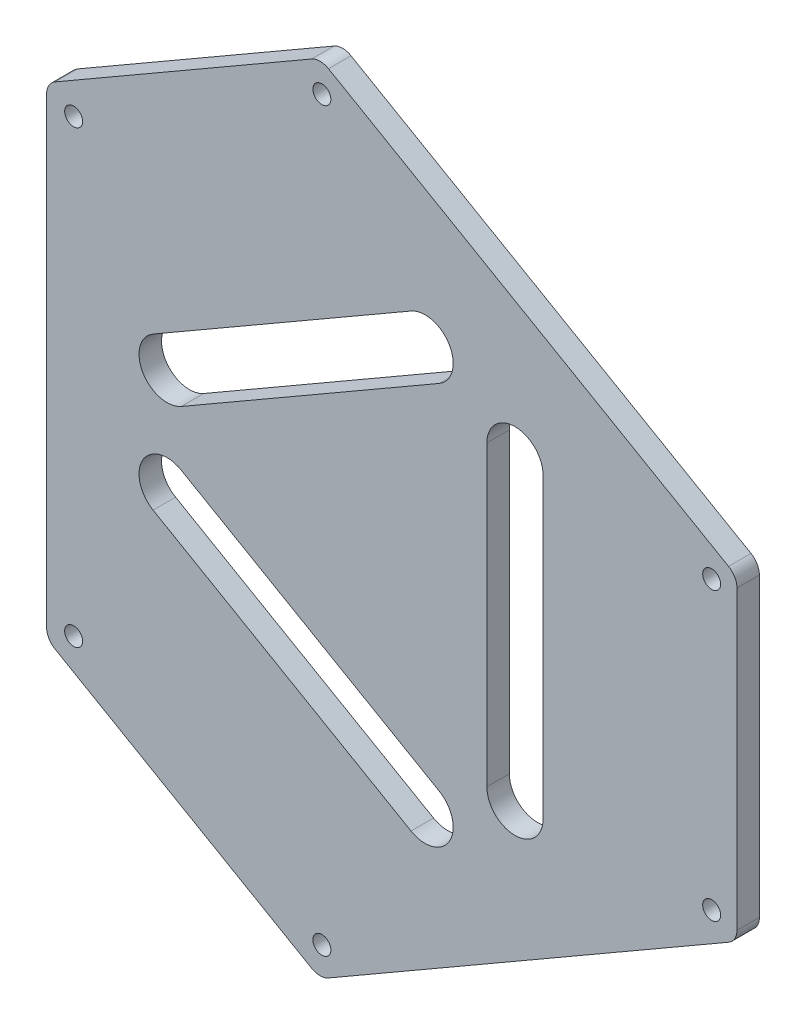
SolidWorks part; units mm, degrees
material "有机玻璃 (TM) GS 丙烯酸铸钣"
ref_plane "前视基准面" through (0, 0, 0) normal (0, 0, 1) x (1, 0, 0)
ref_plane "上视基准面" through (0, 0, 0) normal (0, 1, 0) x (1, 0, 0)
ref_plane "右视基准面" through (0, 0, 0) normal (1, 0, 0) x (0, 0, -1)
sketch "草图1" plane through (0, 0, 0) normal (0, 0, 1) x (1, 0, 0)
  line L0 (0, 0) -> (-67.3124, 0) construction
  line L1 (134.6248, 0) -> (-67.3124, 116.5885)
  line L2 (-67.3124, 116.5885) -> (-67.3124, -116.5885)
  line L3 (-67.3124, -116.5885) -> (134.6248, 0)
  line L4 (-67.3124, 116.5885) -> (-67.3124, 85.5885) construction
  line L5 (-67.3124, 85.5885) -> (-67.3124, 45.5885) construction
  line L6 (0, 0) -> (117.3042, 0) construction
  line L7 (117.3042, 10) -> (117.3042, -10)
  line L8 (-49.9919, -106.5885) -> (-67.3124, -96.5885)
  line L9 (-58.6521, -101.5885) -> (-67.3124, -116.5885) construction
  line L10 (0, 0) -> (-58.6521, -101.5885) construction
  line L11 (-67.3124, 96.5885) -> (-49.9919, 106.5885)
  line L12 (85.9645, 5) -> (-38.6521, 76.9474)
  line L13 (-47.3124, 71.9474) -> (-47.3124, -71.9474)
  line L14 (-38.6521, -76.9474) -> (85.9645, -5)
  line L15 (85.9645, 5) -> (85.9645, -5)
  line L16 (-38.6521, -76.9474) -> (-47.3124, -71.9474)
  line L17 (-47.3124, 71.9474) -> (-38.6521, 76.9474)
  line L18 (94.6248, 0) -> (-47.3124, 81.9474) construction
  line L19 (-47.3124, 81.9474) -> (-47.3124, -81.9474) construction
  line L20 (-47.3124, -81.9474) -> (94.6248, 0) construction
  line L24 (117.3042, 0) -> (134.6248, 0) construction
  line L25 (-58.6521, 101.5885) -> (-67.3124, 116.5885) construction
  line L26 (0, 0) -> (-58.6521, 101.5885) construction
  line L27 (60.9645, -25.5) -> (60.9645, 25.5) construction
  line L28 (60.9645, 0) -> (40.4645, 0) construction
  line L29 (81.4645, 4.5) -> (81.4645, 7.5981)
  line L30 (81.4645, -4.5) -> (81.4645, -7.5981)
  line L31 (35.9645, 33.8675) -> (35.9645, -33.8675)
  line L32 (44.9645, 28.6714) -> (44.9645, -28.6714)
  line L33 (11.3479, -48.0799) -> (-47.3124, -14.2124)
  line L34 (2.3479, -53.2761) -> (-47.3124, -24.6047)
  line L35 (-52.5659, -40.0468) -> (-8.3986, -65.5468) construction
  line L36 (-44.6294, -68.3003) -> (-47.3124, -66.7513)
  line L37 (-36.8351, -72.8003) -> (-34.1521, -74.3494)
  line L38 (-47.3124, 14.2124) -> (11.3479, 48.0799)
  line L39 (-47.3124, 24.6047) -> (2.3479, 53.2761)
  line L40 (-8.3986, 65.5468) -> (-52.5659, 40.0468) construction
  line L41 (-36.8351, 72.8003) -> (-34.1521, 74.3494)
  line L42 (-44.6294, 68.3003) -> (-47.3124, 66.7513)
  line L43 (40.4645, 22) -> (40.4645, -22) construction
  line L44 (60.9645, 25.5) -> (41.9119, 36.5) construction
  line L45 (-8.3986, -65.5468) -> (10.654, -54.5468) construction
  line L46 (-1.1797, -46.0433) -> (-39.2848, -24.0433) construction
  line L47 (-52.5659, 40.0468) -> (-52.5659, 18.0468) construction
  line L48 (-39.2848, 24.0433) -> (-1.1797, 46.0433) construction
  line L49 (65.4645, 28.0981) -> (65.4645, -28.0981)
  line L50 (-8.7186, -70.9277) -> (-57.3859, -42.8296)
  line L51 (-57.3859, 42.8296) -> (-8.7186, 70.9277)
  line L52 (65.4645, 28.0981) -> (-8.7186, 70.9277)
  line L53 (-57.3859, 42.8296) -> (-57.3859, -42.8296)
  line L54 (65.4645, -28.0981) -> (-8.7186, -70.9277)
  line L55 (25.9645, 26.5) -> (25.9645, -26.5) construction
  line L56 (30.9645, 26.5) -> (30.9645, -26.5)
  line L57 (20.9645, 26.5) -> (20.9645, -26.5)
  line L58 (9.9674, -35.7359) -> (-35.9319, -9.2359) construction
  line L59 (7.4674, -40.066) -> (-38.4319, -13.566)
  line L60 (12.4674, -31.4058) -> (-33.4319, -4.9058)
  line L61 (-35.9319, 9.2359) -> (9.9674, 35.7359) construction
  line L62 (-38.4319, 13.566) -> (7.4674, 40.066)
  line L63 (-33.4319, 4.9058) -> (12.4674, 31.4058)
  circle A0 centre (0, 0) radius 67.3124 construction
  circle A1 centre (-59.9021, 103.7535) radius 2.5
  circle A2 centre (-59.9021, 103.7535) radius 10.3078
  circle A3 centre (119.8042, 0) radius 10.3078
  circle A4 centre (119.8042, 0) radius 2.5
  circle A5 centre (-59.9021, -103.7535) radius 10.3078
  circle A6 centre (-59.9021, -103.7535) radius 2.5
  circle A7 centre (40.4645, 0) radius 1.6
  circle A8 centre (60.9645, 25.5) radius 1.6
  circle A9 centre (81.4645, 0) radius 1.6
  circle A10 centre (81.4645, 0) radius 4.5
  circle A11 centre (60.9645, -25.5) radius 1.6
  circle A12 centre (-20.2323, -35.0433) radius 1.6
  circle A13 centre (-8.3986, -65.5468) radius 1.6
  circle A14 centre (-52.5659, -40.0468) radius 1.6
  circle A15 centre (-40.7323, -70.5503) radius 4.5
  circle A16 centre (-40.7323, -70.5503) radius 1.6
  circle A17 centre (-20.2323, 35.0433) radius 1.6
  circle A18 centre (-52.5659, 40.0468) radius 1.6
  circle A19 centre (-8.3986, 65.5468) radius 1.6
  circle A20 centre (-40.7323, 70.5503) radius 4.5
  circle A21 centre (-40.7323, 70.5503) radius 1.6
  circle A22 centre (40.4645, -22) radius 1.6
  circle A23 centre (40.4645, 22) radius 1.6
  circle A24 centre (41.9119, 36.5) radius 1.6
  circle A25 centre (41.9119, -36.5) radius 1.6
  circle A26 centre (-52.5659, -18.0468) radius 1.6
  circle A27 centre (10.654, -54.5468) radius 1.6
  circle A28 centre (-39.2848, -24.0433) radius 1.6
  circle A29 centre (-1.1797, -46.0433) radius 1.6
  circle A30 centre (10.654, 54.5468) radius 1.6
  circle A31 centre (-52.5659, 18.0468) radius 1.6
  circle A32 centre (-1.1797, 46.0433) radius 1.6
  circle A33 centre (-39.2848, 24.0433) radius 1.6
  arc A34 (30.9645, 26.5) -> (20.9645, 26.5) centre (25.9645, 26.5) ccw
  arc A35 (20.9645, -26.5) -> (30.9645, -26.5) centre (25.9645, -26.5) ccw
  arc A36 (7.4674, -40.066) -> (12.4674, -31.4058) centre (9.9674, -35.7359) ccw
  arc A37 (-33.4319, -4.9058) -> (-38.4319, -13.566) centre (-35.9319, -9.2359) ccw
  arc A38 (-38.4319, 13.566) -> (-33.4319, 4.9058) centre (-35.9319, 9.2359) ccw
  arc A39 (12.4674, 31.4058) -> (7.4674, 40.066) centre (9.9674, 35.7359) ccw
  point P13 (117.3042, 0)
  point P21 (0, 0)
  point P26 (85.9645, 0)
  point P33 (0, 0)
  point P36 (0, 0)
  point P45 (0, 0)
  point P98 (0, 0)
  point P126 (0, 0)
  point P127 (65.4645, 0)
  point P133 (-0.2133, 0)
  point P134 (25.9645, 0)
  point P143 (-12.9823, -22.4859)
  point P150 (-12.9823, 22.4859)
  point P155 (0, 0)
  dimension "D9" = 5
  dimension "D10" = 20.6155
  dimension "D14" = 3.2
  dimension "D15" = 9
  dimension "D19" = 22
  dimension "D1" = 233.1769
  dimension "D2" = 31
  dimension "D3" = 40
  dimension "D4" = 20
  dimension "D7" = 10
  dimension "D5" = 3
  dimension "D12" = 25.5
  dimension "D13" = 20.5
  dimension "D16" = 4.5
  dimension "D17" = 4.5
  dimension "D20" = 22
  dimension "D22" = 4.5
  dimension "D23" = 3
  dimension "D24" = 4.5
  dimension "D25" = 53
  dimension "D26" = 10
  dimension "D27" = 3
  dimension "D28" = 15
  dimension "D6" = 20
  dimension "D8" = 3
  dimension "D11" = 3
  dimension "D18" = 3
  dimension "D21" = 3
ref_plane "基准面4" through (-67.3124, 0, 0) normal (1, 0, 0) x (0, 0, -1)
extrude "凸台-拉伸1" add sketch "草图1" along normal blind 4 contours A39 L63 A38 L38 L13 L33 A37 L60 A36 L14 L31 A35 L57 A34 L12 | L49 L12 L32 L14 | L49 L52 L51 L12 A19 A8 A24 A30 | L32 L12 L31 L14 A7 A22 A23 | L54 L49 L14 L50 A27 A11 A13 A25 | L50 L14 L34 L13 | L34 L14 L33 L13 A12 A28 A29 | L51 L53 L50 L13 A31 A14 A18 A26 | L51 L13 L39 L12 | L39 L13 L38 L12 A17 A32 A33 | A32 | A30 | A17 | A33 | A31 | A26 | A28 | A12 | A29 | A27 | A25 | A22 | A7 | A23 | A24 | L3 L1 L2
fillet "圆角1" radius 3 6 edges at (65.4645, 28.0981, 2) (-8.7186, 70.9277, 2) (-57.3859, 42.8296, 2) (-57.3859, -42.8296, 2) (-8.7186, -70.9277, 2) (65.4645, -28.0981, 2)
